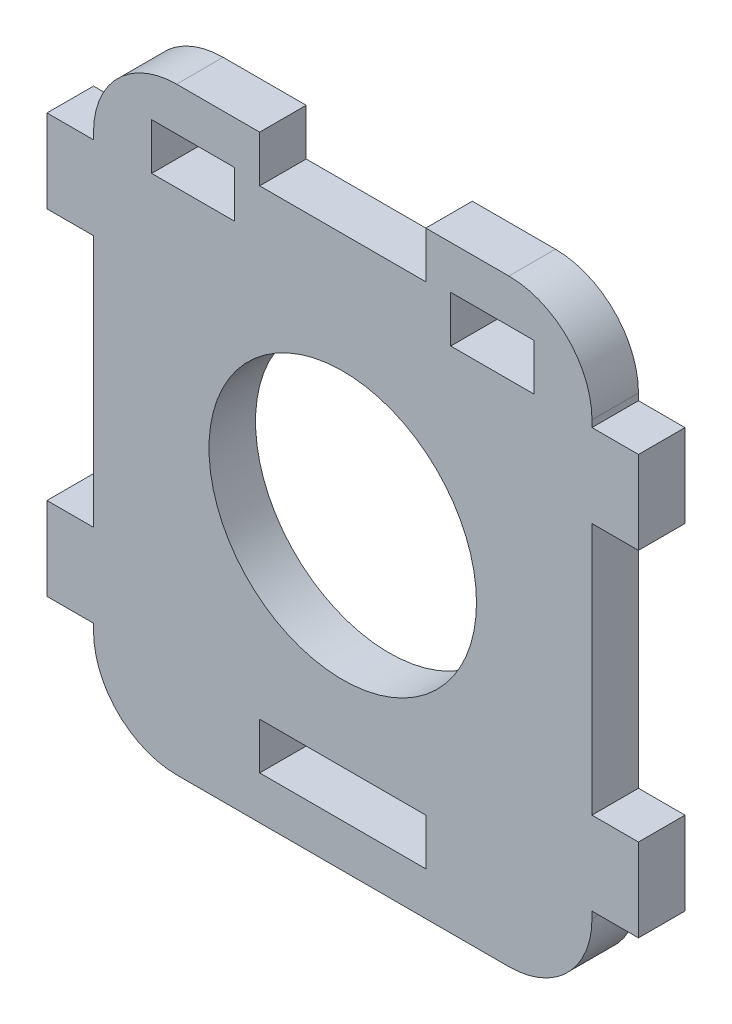
SolidWorks part; units mm, degrees
material "Фанера"
ref_plane "Front Plane" through (0, 0, 0) normal (0, 0, 1) x (1, 0, 0)
ref_plane "Top Plane" through (0, 0, 0) normal (0, 1, 0) x (1, 0, 0)
ref_plane "Right Plane" through (0, 0, 0) normal (1, 0, 0) x (0, 0, -1)
sketch "Эскиз1" plane through (0, 0, 0) normal (0, 0, 1) x (1, 0, 0)
  line L0 (-15, 12.6) -> (-17.8, 12.6)
  line L1 (-15, -18) -> (15, -18)
  line L2 (-15, -18) -> (-15, -12.6)
  line L3 (-15, 18) -> (-5, 18)
  line L4 (15, -18) -> (15, -12.6)
  line L5 (-15, -18) -> (15, 18) construction
  line L6 (-15, 18) -> (15, -18) construction
  line L7 (-17.8, 12.6) -> (-17.8, 7.6)
  line L8 (-17.8, 7.6) -> (-15, 7.6)
  line L9 (-24.8552, 0) -> (28.9627, 0) construction
  line L10 (0, 23.0741) -> (0, -18.911) construction
  line L11 (-15, 12.6) -> (-15, 18)
  line L12 (17.8, 7.6) -> (15, 7.6)
  line L13 (17.8, 12.6) -> (17.8, 7.6)
  line L14 (15, 12.6) -> (17.8, 12.6)
  line L15 (15, 12.6) -> (15, 18)
  line L16 (15, -12.6) -> (17.8, -12.6)
  line L17 (17.8, -12.6) -> (17.8, -7.6)
  line L18 (17.8, -7.6) -> (15, -7.6)
  line L19 (-17.8, -7.6) -> (-15, -7.6)
  line L20 (-17.8, -12.6) -> (-17.8, -7.6)
  line L21 (-15, -12.6) -> (-17.8, -12.6)
  line L22 (-15, -7.6) -> (-15, 7.6)
  line L23 (15, -7.6) -> (15, 7.6)
  line L24 (5, -15.4) -> (-5, -15.4)
  line L29 (11.5, 15.4) -> (6.5, 15.4)
  line L30 (-11.5, 12.6) -> (-6.5, 12.6)
  line L31 (-5, -12.6) -> (-5, -15.4)
  line L32 (5, -12.6) -> (-5, -12.6)
  line L33 (5, -12.6) -> (5, -15.4)
  line L34 (-11.5, 12.6) -> (-11.5, 15.4)
  line L35 (-11.5, 15.4) -> (-6.5, 15.4)
  line L36 (-6.5, 12.6) -> (-6.5, 15.4)
  line L37 (-11.5, 12.6) -> (-6.5, 15.4) construction
  line L38 (-11.5, 15.4) -> (-6.5, 12.6) construction
  line L39 (6.5, 12.6) -> (6.5, 15.4)
  line L40 (11.5, 12.6) -> (6.5, 12.6)
  line L41 (11.5, 12.6) -> (11.5, 15.4)
  line L42 (5, 18) -> (15, 18)
  line L44 (-5, 18) -> (-5, 15.2)
  line L45 (-5, 15.2) -> (5, 15.2)
  line L46 (5, 18) -> (5, 15.2)
  line L47 (0, 18) -> (5, 15.2) construction
  line L48 (-5, 15.2) -> (0, 18) construction
  circle A0 centre (0, 0) radius 8.05
  point P0 (0, 0)
  point P28 (0, 14)
  point P29 (-9, 14)
  point P38 (-11.5, 14)
  point P45 (0, 18)
  dimension "D2" = 16.1
  dimension "D1" = 30
  dimension "D3" = 36
  dimension "D4" = 5
  dimension "D5" = 2.8
  dimension "D6" = 5.4
  dimension "D7" = 2.8
  dimension "D8" = 5
  dimension "D9" = 6
  dimension "D10" = 2.8
  dimension "D11" = 10
  dimension "D12" = 5
extrude "Бобышка-Вытянуть1" add sketch "Эскиз1" along normal mid plane 2.8
fillet "Скругление1" radius 5 4 edges at (-15, 18, 0) (15, -18, 0) (-15, -18, 0) (15, 18, 0)
